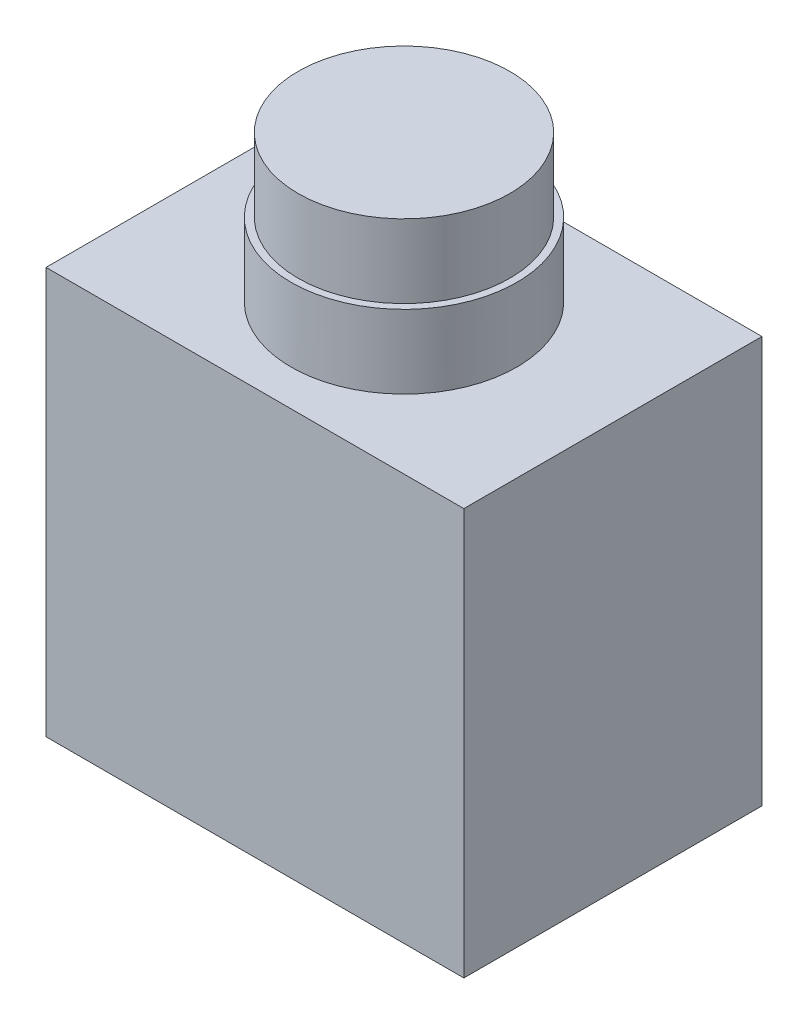
SolidWorks part; units mm, degrees
ref_plane "Front Plane" through (0, 0, 0) normal (0, 0, 1) x (1, 0, 0)
ref_plane "Top Plane" through (0, 0, 0) normal (0, 1, 0) x (1, 0, 0)
ref_plane "Right Plane" through (0, 0, 0) normal (1, 0, 0) x (0, 0, -1)
sketch "Sketch1" plane through (0, 0, 0) normal (0, 1, 0) x (1, 0, 0)
  line L1 (0, 0) -> (23.495, 0)
  line L2 (0, 0) -> (0, 16.764)
  line L3 (0, 16.764) -> (23.495, 16.764)
  line L4 (23.495, 0) -> (23.495, 16.764)
  dimension "D1" = 16.764
  dimension "D2" = 23.495
extrude "Boss-Extrude1" add sketch "Sketch1" along normal blind 22.86
sketch "Sketch2" plane through (0, 22.86, 0) normal (0, 1, 0) x (1, 0, 0)
  line L0 (0, 8.382) -> (23.495, 8.382) construction
  line L1 (0, 16.764) -> (0, 0) construction
  line L2 (23.495, 0) -> (23.495, 16.764) construction
  line L3 (11.7475, 16.764) -> (11.7475, 0) construction
  line L4 (23.495, 16.764) -> (0, 16.764) construction
  line L5 (0, 0) -> (23.495, 0) construction
  circle A0 centre (11.7475, 8.382) radius 6.35
  dimension "D1" = 12.7
extrude "Boss-Extrude2" add sketch "Sketch2" along normal blind 4.1275
sketch "Sketch3" plane through (0, 26.9875, 0) normal (0, 1, 0) x (1, 0, 0)
  circle A0 centre (11.7475, 8.382) radius 5.9531
  circle A1 centre (11.7475, 8.382) radius 6.35 construction
  circle A2 centre (11.7475, 8.382) radius 6.35 construction
  dimension "D1" = 11.9062
extrude "Boss-Extrude3" add sketch "Sketch3" along normal blind 4.1275
